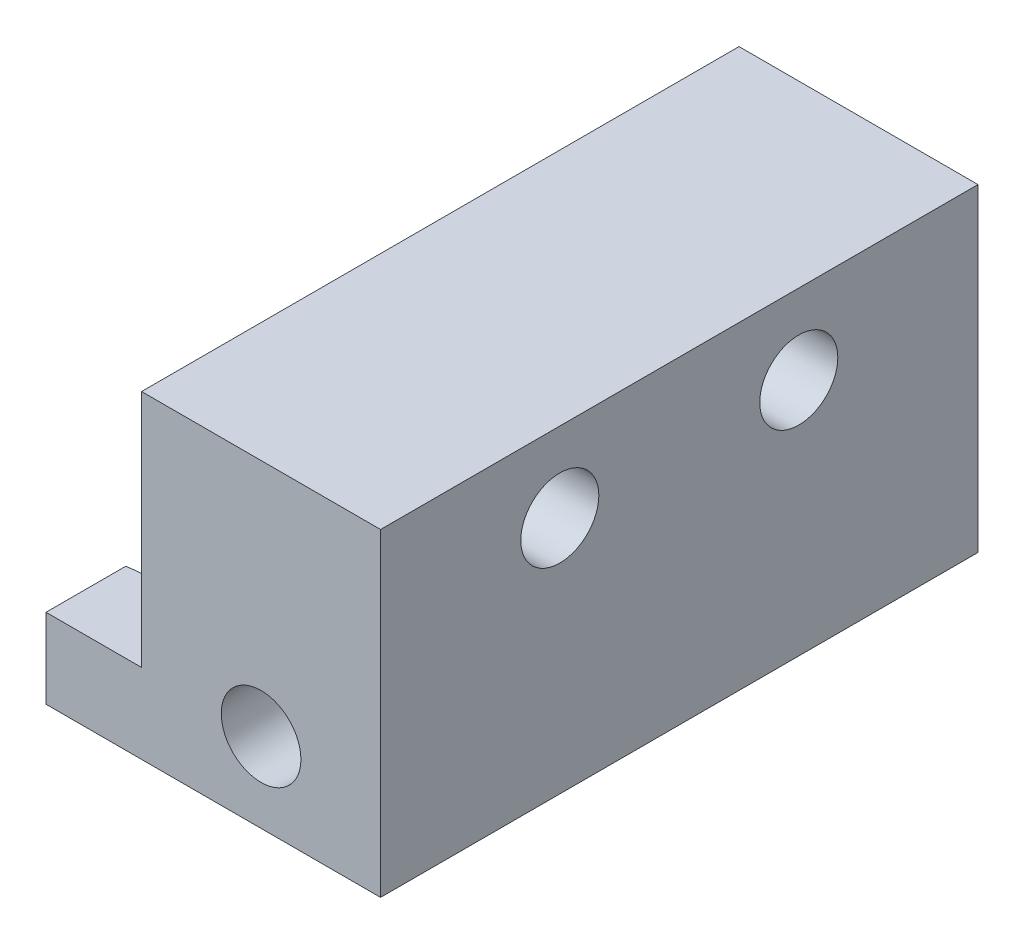
SolidWorks part; units mm, degrees
ref_plane "Front Plane" through (0, 0, 0) normal (0, 0, 1) x (1, 0, 0)
ref_plane "Top Plane" through (0, 0, 0) normal (0, 1, 0) x (1, 0, 0)
ref_plane "Right Plane" through (0, 0, 0) normal (1, 0, 0) x (0, 0, -1)
sketch "Sketch1" plane through (0, 0, 0) normal (0, 1, 0) x (1, 0, 0)
  line L1 (-15, 37.5) -> (15, 37.5)
  line L2 (-15, 37.5) -> (-15, -37.5)
  line L3 (-15, -37.5) -> (15, -37.5)
  line L4 (15, 37.5) -> (15, -37.5)
  line L5 (-15, 37.5) -> (15, -37.5) construction
  line L6 (-15, -37.5) -> (15, 37.5) construction
  point P0 (0, 0)
  dimension "D1" = 30
  dimension "D2" = 75
extrude "Main Block" add sketch "Sketch1" along normal mid plane 40
sketch "Sketch2" plane through (0, 0, 37.5) normal (0, 0, 1) x (1, 0, 0)
  line L0 (0, -55) -> (0, 55) construction
  line L1 (-15, -20) -> (15, -20) construction
  circle A0 centre (0, -10) radius 5
  dimension "D1" = 10
  dimension "D2" = 10
extrude "Frame Hole" cut sketch "Sketch2" against normal up to next
sketch "EM Rod Holes Sketch" plane through (15, 0, 0) normal (1, 0, 0) x (0, 0, -1)
  line L0 (-37.5, 20) -> (37.5, 20) construction
  line L1 (0, 11) -> (0, -11) construction
  circle A0 centre (-15, 10) radius 4.9
  circle A1 centre (15, 10) radius 4.9
  dimension "D1" = 9.8
  dimension "D4" = 9.8
  dimension "D2" = 10
  dimension "D3" = 15
  dimension "D5" = 10
  dimension "D6" = 15
extrude "EM Rod Holes" cut sketch "EM Rod Holes Sketch" against normal up to next
sketch "Sketch4" plane through (0, -20, 0) normal (0, -1, 0) x (1, 0, 0)
  line L10 (15, -37.5) -> (-15, -37.5) construction
  line L11 (-15, 37.5) -> (-27, 37.5)
  line L12 (-15, 37.5) -> (-15, -37.5)
  line L13 (-15, -37.5) -> (-27, -37.5)
  line L14 (-27, 37.5) -> (-27, -37.5)
  dimension "D1" = 12
extrude "Boss-Extrude1" add sketch "Sketch4" against normal blind 10
sketch "Sketch6" plane through (0, -20, 0) normal (0, -1, 0) x (1, 0, 0)
  line L0 (-27, 26.5) -> (-15, 26.5) construction
  line L1 (-27, 27.5) -> (-15, 27.5)
  line L2 (-27, 27.5) -> (-27, 25.5)
  line L3 (-27, 25.5) -> (-15, 25.5)
  line L4 (-15, 27.5) -> (-15, 25.5)
  line L5 (-27, 27.5) -> (-15, 25.5) construction
  line L6 (-27, 25.5) -> (-15, 27.5) construction
  line L7 (-27, 27.3) -> (-15, 27.3) construction
  line L8 (-27, 25.6) -> (-15, 25.6) construction
  line L10 (-27, 37.5) -> (15, 37.5) construction
  line L12 (-27, 37.5) -> (-27, -37.5) construction
  arc A0 (-27, 27.5) -> (-25, 27.3) centre (-25, 37.4) ccw
  arc A1 (-25, 27.3) -> (-24.8, 27.5) centre (-25, 27.5) ccw
  arc A2 (-27, 25.5) -> (-25, 25.7) centre (-25, 15.6) cw
  arc A3 (-25, 25.7) -> (-24.8, 25.5) centre (-25, 25.5) cw
  point P0 (-21, 26.5)
  point P21 (-23.983, 27.5)
  line M12 (-27, 37.5) -> (-27, -37.5)
  dimension "D1" = 12
  dimension "D2" = 2
  dimension "D3" = 0.2
  dimension "D4" = 0.2
  dimension "D5" = 2
  dimension "D6" = 10
extrude "Cut-Extrude1" cut sketch "Sketch6" against normal through all both contours A2 A3 L3 L4 L1 A1 A0 M12
mirror "Mirror1" about plane through (0, 0, 0) normal (0, 0, 1) of "Cut-Extrude1"
